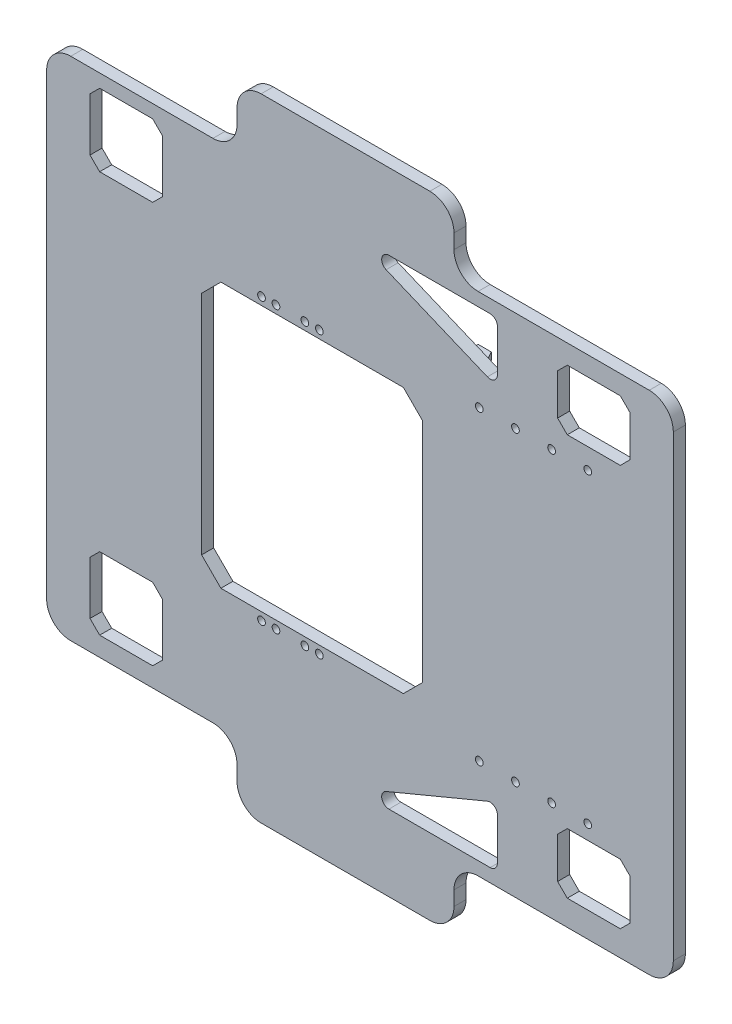
SolidWorks part; units mm, degrees
ref_plane "前视基准面" through (0, 0, 0) normal (0, 0, 1) x (1, 0, 0)
ref_plane "上视基准面" through (0, 0, 0) normal (0, 1, 0) x (1, 0, 0)
ref_plane "右视基准面" through (0, 0, 0) normal (1, 0, 0) x (0, 0, -1)
sketch "草图1" plane through (0, 0, 0) normal (0, 0, 1) x (1, 0, 0)
  line L0 (-51, 115) -> (-51, 121)
  line L1 (-120, 105) -> (-61, 105)
  line L2 (-130, 95) -> (-130, -95)
  line L3 (-120, -105) -> (-61, -105)
  line L4 (130, 95) -> (130, -95)
  line L5 (-130, 105) -> (-126.7518, 102.3765) construction
  line L6 (-130, -105) -> (-126.7518, -102.3765) construction
  line L7 (-41, 131) -> (29, 131)
  line L8 (39, 121) -> (39, 115)
  line L9 (-51, -115) -> (-51, -121)
  line L10 (-41, -131) -> (29, -131)
  line L11 (39, -121) -> (39, -115)
  line L12 (49, 105) -> (120, 105)
  line L13 (49, -105) -> (120, -105)
  line L14 (126.7518, -102.3765) -> (130, -105) construction
  line L15 (126.7518, 102.3765) -> (130, 105) construction
  arc A0 (-130, 95) -> (-120, 105) centre (-120, 95) cw
  arc A1 (-120, -105) -> (-130, -95) centre (-120, -95) cw
  arc A2 (130, 95) -> (120, 105) centre (120, 95) ccw
  arc A3 (120, -105) -> (130, -95) centre (120, -95) ccw
  arc A4 (-61, 105) -> (-51, 115) centre (-61, 115) ccw
  arc A5 (49, 105) -> (39, 115) centre (49, 115) cw
  arc A6 (-41, 131) -> (-51, 121) centre (-41, 121) ccw
  arc A7 (39, 121) -> (29, 131) centre (29, 121) ccw
  arc A8 (-51, -115) -> (-61, -105) centre (-61, -115) ccw
  arc A9 (39, -115) -> (49, -105) centre (49, -115) cw
  arc A10 (-41, -131) -> (-51, -121) centre (-41, -121) cw
  arc A11 (29, -131) -> (39, -121) centre (29, -121) ccw
  point P0 (0, 0)
  point P28 (-45.35, 105)
  point P32 (39, 105)
  point P40 (39, -105)
  dimension "D1" = 10
  dimension "D2" = 10
  dimension "D3" = 10
  dimension "D4" = 10
  dimension "D5" = 10
  dimension "D6" = 10
  dimension "D9" = 10
  dimension "D11" = 10
  dimension "D7" = 10
  dimension "D8" = 10
  dimension "D10" = 10
  dimension "D12" = 10
  dimension "D13" = 210
  dimension "D14" = 59
  dimension "D15" = 71
  dimension "D16" = 59
  dimension "D17" = 71
  dimension "D18" = 70
  dimension "D19" = 6
  dimension "D20" = 6
extrude "凸台-拉伸1" add sketch "草图1" along normal blind 5
sketch "草图2" plane through (0, 0, 5) normal (0, 0, 1) x (1, 0, 0)
  line L0 (130, -95) -> (130, 95) construction
  line L5 (10.8462, -93.7308) -> (52.8462, -76.2308)
  line L6 (-108, 99.5) -> (-86, 99.5)
  line L7 (-108, -67) -> (-86, -67)
  line L8 (-112, -71) -> (-112, -93)
  line L9 (-108, -97) -> (-86, -97)
  line L10 (-82, -71) -> (-82, -93)
  line L11 (-112, -67) -> (-82, -97) construction
  line L12 (-112, -97) -> (-82, -67) construction
  line L13 (86, 97) -> (108, 97)
  line L14 (82, 93) -> (82, 76)
  line L15 (86, 72) -> (108, 72)
  line L16 (112, 93) -> (112, 76)
  line L17 (82, 97) -> (112, 72) construction
  line L18 (82, 72) -> (112, 97) construction
  line L19 (86, -69.5) -> (108, -69.5)
  line L20 (82, -73.5) -> (82, -90.5)
  line L21 (86, -94.5) -> (108, -94.5)
  line L22 (112, -73.5) -> (112, -90.5)
  line L23 (82, -69.5) -> (112, -94.5) construction
  line L24 (82, -94.5) -> (112, -69.5) construction
  line L25 (12, 99.5) -> (54, 99.5)
  line L28 (57, 96.5) -> (57, 79)
  line L29 (10.8462, 93.7308) -> (52.8462, 76.2308)
  line L33 (12, -99.5) -> (54, -99.5)
  line L34 (57, -79) -> (57, -96.5)
  line L35 (-41, -131) -> (29, -131) construction
  line L37 (-112, 95.5) -> (-112, 73.5)
  line L38 (-120, -105) -> (-61, -105) construction
  line L39 (-130, 95) -> (-130, -95) construction
  line L40 (-108, 69.5) -> (-86, 69.5)
  line L41 (-82, 95.5) -> (-82, 73.5)
  line L42 (-112, 99.5) -> (-82, 69.5) construction
  line L43 (-112, 69.5) -> (-82, 99.5) construction
  line L44 (-112, 73.5) -> (-108, 69.5)
  line L45 (-112, 95.5) -> (-108, 99.5)
  line L46 (-86, 69.5) -> (-82, 73.5)
  line L47 (-86, 99.5) -> (-82, 95.5)
  line L48 (-108, -67) -> (-112, -71)
  line L49 (-112, -93) -> (-108, -97)
  line L50 (-86, -67) -> (-82, -71)
  line L51 (-86, -97) -> (-82, -93)
  line L52 (86, 97) -> (82, 93)
  line L53 (82, 76) -> (86, 72)
  line L54 (108, 97) -> (112, 93)
  line L55 (108, 72) -> (112, 76)
  line L56 (86, -69.5) -> (82, -73.5)
  line L57 (108, -69.5) -> (112, -73.5)
  line L58 (82, -90.5) -> (86, -94.5)
  line L59 (108, -94.5) -> (112, -90.5)
  arc A0 (57, -96.5) -> (54, -99.5) centre (54, -96.5) cw
  arc A1 (57, -79) -> (52.8462, -76.2308) centre (54, -79) ccw
  arc A2 (12, -99.5) -> (10.8462, -93.7308) centre (12, -96.5) cw
  arc A3 (10.8462, 93.7308) -> (12, 99.5) centre (12, 96.5) cw
  arc A4 (57, 96.5) -> (54, 99.5) centre (54, 96.5) ccw
  arc A5 (57, 79) -> (52.8462, 76.2308) centre (54, 79) cw
  point P0 (-97, 84.5)
  point P1 (-97, 84.5)
  point P5 (-97, -82)
  point P10 (97, 84.5)
  point P15 (97, -82)
  point P20 (27, 84.5)
  point P25 (27, -82)
  point P75 (-3, 99.5)
  point P78 (57, 99.5)
  dimension "D11" = 3
  dimension "D17" = 3
  dimension "D18" = 3
  dimension "D35" = 3
  dimension "D36" = 3
  dimension "D37" = 3
  dimension "D2" = 8
  dimension "D3" = 18
  dimension "D4" = 30
  dimension "D5" = 25
  dimension "D6" = 30
  dimension "D7" = 18
  dimension "D8" = 18
  dimension "D9" = 25
  dimension "D10" = 30
  dimension "D12" = 60
  dimension "D13" = 25
  dimension "D14" = 30
  dimension "D15" = 25
  dimension "D19" = 42
  dimension "D20" = 17.5
  dimension "D38" = 17.5
  dimension "D39" = 31.5
extrude "切除-拉伸1" cut sketch "草图2" against normal through all
sketch "草图3" plane through (0, 0, 0) normal (0, 0, -1) x (-1, 0, 0)
  line L0 (130, 95) -> (130, -95) construction
  line L1 (57.7, 55) -> (-18, 55)
  line L2 (65.7, 47) -> (65.7, -47)
  line L3 (57.7, -55) -> (-18, -55)
  line L4 (-26, 47) -> (-26, -47)
  line L5 (65.7, 55) -> (-26, -55) construction
  line L6 (65.7, -55) -> (-26, 55) construction
  line L7 (-26, -47) -> (-18, -55)
  line L8 (-18, 55) -> (-26, 47)
  line L9 (65.7, -47) -> (57.7, -55)
  line L10 (57.7, 55) -> (65.7, 47)
  point P0 (19.85, 0)
  dimension "D1" = 64.3
  dimension "D2" = 91.7
  dimension "D3" = 110
extrude "切除-拉伸2" cut sketch "草图3" against normal through all
sketch "草图4" plane through (0, 0, 0) normal (0, 0, -1) x (-1, 0, 0)
  line L0 (-29, -55) -> (-29, -66)
  line L1 (-29, -66) -> (-40, -66)
  line L2 (-40, -66) -> (-40, -63)
  line L3 (-40, -63) -> (-32, -63)
  line L4 (-32, -63) -> (-32, -55)
  line L5 (-32, -55) -> (-29, -55)
  line L6 (-26, 47) -> (-26, -47) construction
  line L7 (-49, -105) -> (-120, -105) construction
  dimension "D1" = 11
  dimension "D2" = 11
  dimension "D3" = 3
  dimension "D4" = 3
  dimension "D5" = 3
  dimension "D6" = 39
extrude "凸台-拉伸2" add sketch "草图4" along normal blind 15
sketch "草图5" plane through (0, -66, 0) normal (0, -1, 0) x (1, 0, 0)
  line L0 (40, -5) -> (34.5, -15)
  line L1 (40, -15) -> (40, 0) construction
  line L2 (40, -15) -> (29, -15) construction
  line L3 (34.5, -15) -> (40, -15)
  line L4 (40, -15) -> (40, -5)
  dimension "D1" = 10
  dimension "D2" = 5.5
extrude "切除-拉伸3" cut sketch "草图5" against normal blind 10
sketch "草图6" plane through (29, 0, 0) normal (-1, 0, 0) x (0, 0, 1)
  line L0 (-15, -60.5) -> (-5, -55)
  line L1 (-15, -66) -> (-15, -55) construction
  line L2 (-15, -55) -> (0, -55) construction
  line L3 (-5, -55) -> (-15, -55)
  line L4 (-15, -55) -> (-15, -60.5)
  dimension "D1" = 10
  dimension "D2" = 5.5
extrude "切除-拉伸4" cut sketch "草图6" against normal blind 10
ref_plane "基准面2" through (72, 0, 0) normal (-1, 0, 0) x (0, 0, 1)
mirror "镜向1" about plane through (72, 0, 0) normal (-1, 0, 0) of "凸台-拉伸2", "切除-拉伸3", "切除-拉伸4"
mirror "镜向2" about plane through (0, 0, 0) normal (0, 1, 0) of "镜向1", "凸台-拉伸2", "切除-拉伸3", "切除-拉伸4"
sketch "草图7" plane through (0, 0, 0) normal (0, 0, -1) x (-1, 0, 0)
  line L0 (65.7, -47) -> (65.7, 47) construction
  line L1 (-18, -55) -> (57.7, -55) construction
  circle A0 centre (16.85, -58.25) radius 1.6
  circle A1 centre (22.85, -58.25) radius 1.6
  circle A2 centre (40.85, -58.25) radius 1.6
  circle A3 centre (34.85, -58.25) radius 1.6
  point P8 (0, 0)
  dimension "D1" = 3.2
  dimension "D2" = 3.2
  dimension "D3" = 3.2
  dimension "D4" = 3.2
  dimension "D6" = 6
  dimension "D7" = 6
  dimension "D8" = 30.85
  dimension "D9" = 3.25
  dimension "D5" = 18
extrude "切除-拉伸5" cut sketch "草图7" against normal through all
mirror "镜向3" about plane through (0, 0, 0) normal (0, 1, 0) of "切除-拉伸5"
sketch "草图8" plane through (0, 0, 0) normal (0, 0, -1) x (-1, 0, 0)
  line L1 (-40, -63) -> (-40, -66) construction
  circle A0 centre (-49.5, -63.4954) radius 1.6
  circle A1 centre (-64.5, -63.4954) radius 1.6
  circle A2 centre (-79.5, -63.4954) radius 1.6
  circle A3 centre (-94.5, -63.4954) radius 1.6
  point P8 (0, 0)
  dimension "D1" = 3.2
  dimension "D2" = 3.2
  dimension "D3" = 3.2
  dimension "D4" = 3.2
  dimension "D5" = 15
  dimension "D6" = 15
  dimension "D7" = 15
  dimension "D8" = 9.5
extrude "切除-拉伸6" cut sketch "草图8" against normal through all
mirror "镜向4" about plane through (0, 0, 0) normal (0, 1, 0) of "切除-拉伸6"
equation "\"45、\"=43.7672"
